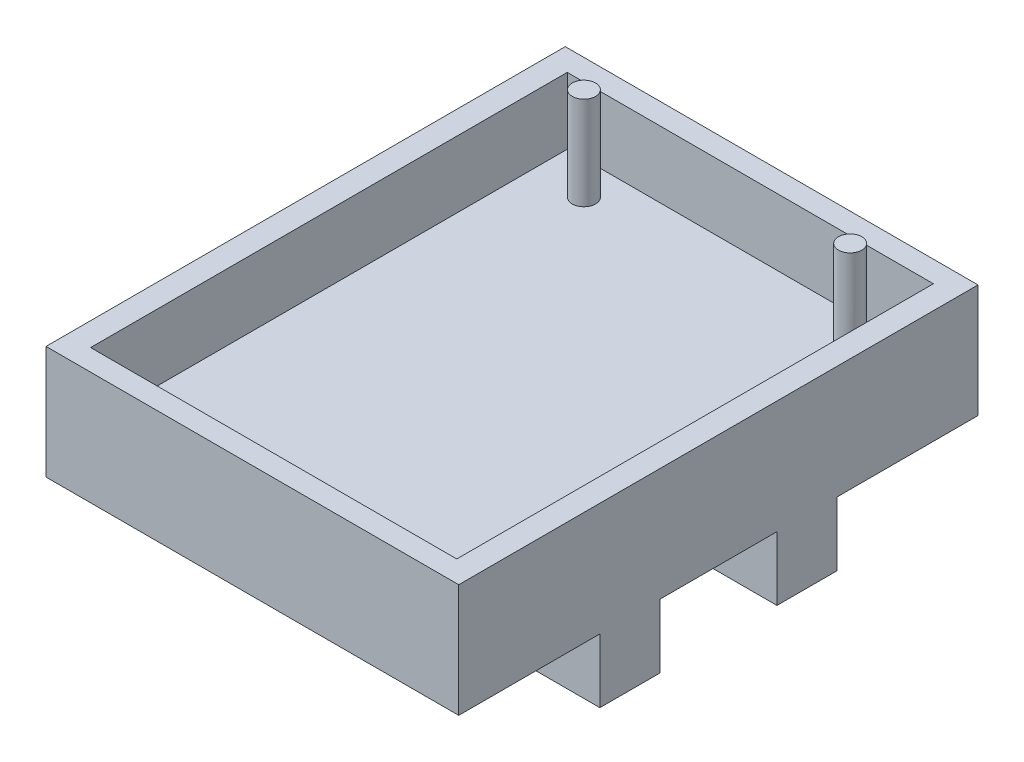
SolidWorks part; units mm, degrees
ref_plane "Front Plane" through (0, 0, 0) normal (0, 0, 1) x (1, 0, 0)
ref_plane "Top Plane" through (0, 0, 0) normal (0, 1, 0) x (1, 0, 0)
ref_plane "Right Plane" through (0, 0, 0) normal (1, 0, 0) x (0, 0, -1)
sketch "Sketch1" plane through (0, 0, 0) normal (0, 1, 0) x (1, 0, 0)
  line L1 (-15.5, -19.5) -> (15.5, -19.5)
  line L2 (-15.5, -19.5) -> (-15.5, 19.5)
  line L3 (-15.5, 19.5) -> (15.5, 19.5)
  line L4 (15.5, -19.5) -> (15.5, 19.5)
  line L5 (-15.5, -19.5) -> (15.5, 19.5) construction
  line L6 (-15.5, 19.5) -> (15.5, -19.5) construction
  point P0 (0, 0)
  dimension "D1" = 31
  dimension "D2" = 39
extrude "Boss-Extrude1" add sketch "Sketch1" along normal blind 8.5
sketch "Sketch5" plane through (0, 0, 0) normal (0, -1, 0) x (1, 0, 0)
  line L0 (0, -4.45) -> (0, 4.45) construction
  line L1 (-15.5, -19.5) -> (-15.5, 19.5) construction
  line L2 (-15.5, 4.4) -> (15.5, 4.4)
  line L3 (-15.5, 4.4) -> (-15.5, 8.9)
  line L4 (-15.5, 8.9) -> (15.5, 8.9)
  line L5 (15.5, 4.4) -> (15.5, 8.9)
  line L6 (15.5, 19.5) -> (15.5, -19.5) construction
  point P4 (0, 0)
  dimension "D1" = 4.5
  dimension "D2" = 8.9
extrude "Boss-Extrude3" add sketch "Sketch5" along normal blind 4.8
mirror "Mirror1" about plane through (0, 0, 0) normal (0, 0, 1) of "Boss-Extrude3"
sketch "Sketch7" plane through (0, 8.5, 0) normal (0, 1, 0) x (1, 0, 0)
  line L1 (-13.75, -17.9) -> (13.75, -17.9)
  line L2 (-13.75, -17.9) -> (-13.75, 17.9)
  line L3 (-13.75, 17.9) -> (13.75, 17.9)
  line L4 (13.75, -17.9) -> (13.75, 17.9)
  line L5 (-13.75, -17.9) -> (13.75, 17.9) construction
  line L6 (-13.75, 17.9) -> (13.75, -17.9) construction
  point P0 (0, 0)
  dimension "D1" = 27.5
  dimension "D2" = 35.8
extrude "Cut-Extrude1" cut sketch "Sketch7" against normal blind 5
sketch "Sketch8" plane through (0, 3.5, 0) normal (0, 1, 0) x (1, 0, 0)
  line L0 (0, 17.9) -> (0, 15.4) construction
  line L1 (13.75, 17.9) -> (-13.75, 17.9) construction
  line L2 (-10, 15.4) -> (10, 15.4) construction
  circle A0 centre (-10, 15.4) radius 0.875
  circle A1 centre (10, 15.4) radius 0.875
  point P8 (0, 15.4)
  dimension "D2" = 1.75
  dimension "D3" = 1.75
  dimension "D1" = 20
extrude "Boss-Extrude4" add sketch "Sketch8" along normal blind 7
